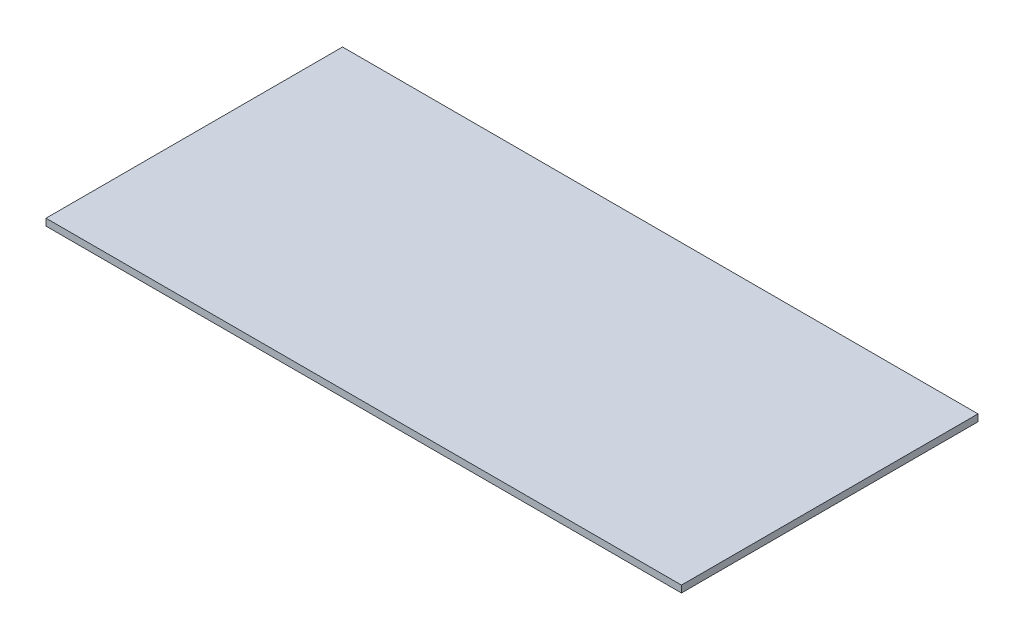
SolidWorks part; units mm, degrees
ref_plane "Front Plane" through (0, 0, 0) normal (0, 0, 1) x (1, 0, 0)
ref_plane "Top Plane" through (0, 0, 0) normal (0, 1, 0) x (1, 0, 0)
ref_plane "Right Plane" through (0, 0, 0) normal (1, 0, 0) x (0, 0, -1)
sketch "Sketch1" plane through (0, 0, 0) normal (0, 1, 0) x (1, 0, 0)
  line L1 (-600, 280) -> (600, 280)
  line L2 (-600, 280) -> (-600, -280)
  line L3 (-600, -280) -> (600, -280)
  line L4 (600, 280) -> (600, -280)
  line L5 (-600, 280) -> (600, -280) construction
  line L6 (-600, -280) -> (600, 280) construction
  point P0 (0, 0)
  dimension "D1" = 1200
  dimension "D2" = 560
extrude "Boss-Extrude1" add sketch "Sketch1" along normal blind 13
